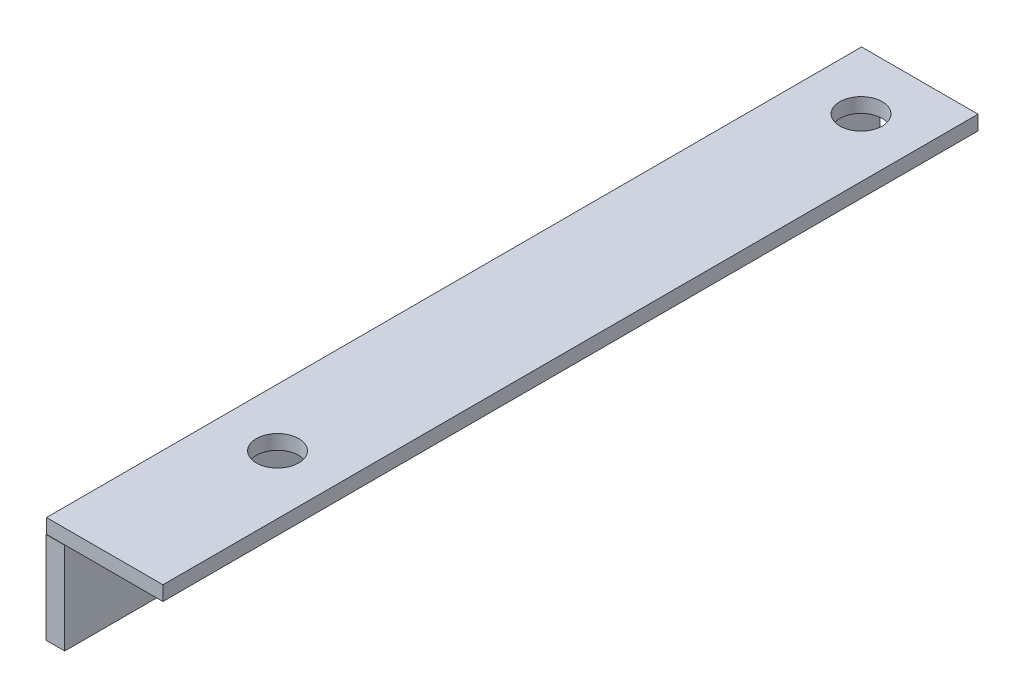
SolidWorks part; units mm, degrees
ref_plane "Front Plane" through (0, 0, 0) normal (0, 0, 1) x (1, 0, 0)
ref_plane "Top Plane" through (0, 0, 0) normal (0, 1, 0) x (1, 0, 0)
ref_plane "Right Plane" through (0, 0, 0) normal (1, 0, 0) x (0, 0, -1)
sketch "Sketch1" plane through (0, 0, 0) normal (0, 1, 0) x (1, 0, 0)
  line L1 (0, 101.5375) -> (12.7, 101.5375)
  line L2 (0, 101.5375) -> (0, 12.6375)
  line L3 (0, 12.6375) -> (12.7, 12.6375)
  line L4 (12.7, 101.5375) -> (12.7, 12.6375)
  circle A0 centre (6.2932, 95.1875) radius 2.31
  circle A5 centre (6.2932, 31.5375) radius 2.31
  dimension "D1" = 12.7
  dimension "D2" = 88.9
extrude "Boss-Extrude1" add sketch "Sketch1" along normal blind 1.5875
sketch "Sketch3" plane through (0, 0, 0) normal (0, -1, 0) x (-1, 0, 0)
  line L0 (-12.7, 101.5375) -> (0, 101.5375) construction
  line L1 (-2.0186, 12.6021) -> (0.0201, 12.6021)
  line L2 (-2.0186, 12.6021) -> (-2.0186, 101.5375)
  line L3 (-2.0186, 101.5375) -> (0.0201, 101.5375)
  line L4 (0.0201, 12.6021) -> (0.0201, 101.5375)
  point P7 (0, 0)
extrude "Boss-Extrude3" add sketch "Sketch3" along normal blind 10
